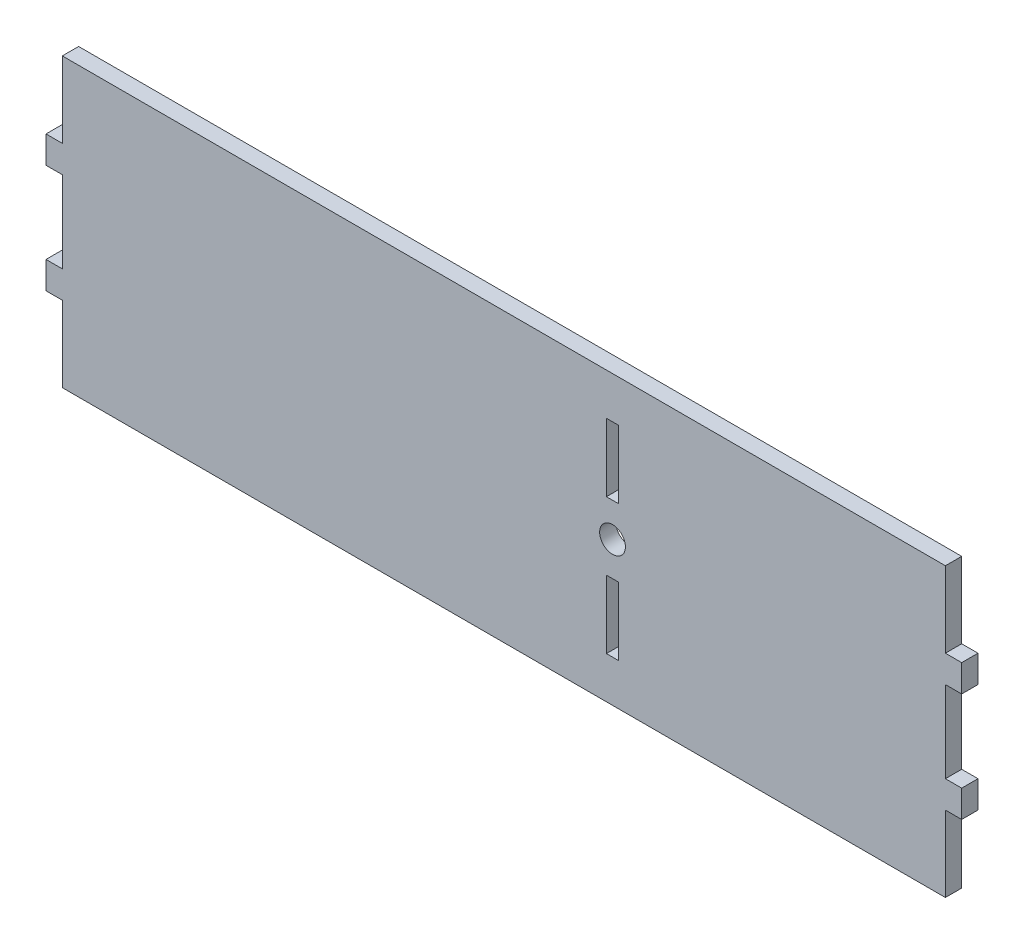
SolidWorks part; units mm, degrees
ref_plane "Front Plane" through (0, 0, 0) normal (0, 0, 1) x (1, 0, 0)
ref_plane "Top Plane" through (0, 0, 0) normal (0, 1, 0) x (1, 0, 0)
ref_plane "Right Plane" through (0, 0, 0) normal (1, 0, 0) x (0, 0, -1)
sketch "Sketch1" plane through (0, 0, 0) normal (0, 0, 1) x (1, 0, 0)
  line L0 (-65, 21.15) -> (-65, 10)
  line L1 (65, 21.15) -> (-65, 21.15)
  line L2 (65, 21.15) -> (65, -21.15)
  line L3 (65, -21.15) -> (-65, -21.15)
  line L4 (-65, 21.15) -> (-65, -21.15)
  line L5 (65, 21.15) -> (-65, -21.15) construction
  line L6 (65, -21.15) -> (-65, 21.15) construction
  line L7 (-65, 10) -> (-67.4, 10)
  line L8 (-67.4, 10) -> (-67.4, 6)
  line L9 (-67.4, 6) -> (-65, 6)
  line L10 (-65, 0) -> (65, 0)
  line L11 (-65, -10) -> (-67.4, -10)
  line L12 (-67.4, -10) -> (-67.4, -6)
  line L13 (-67.4, -6) -> (-65, -6)
  line L14 (0, 21.15) -> (0, -21.15)
  line L15 (65, -10) -> (67.4, -10)
  line L16 (67.4, -10) -> (67.4, -6)
  line L17 (67.4, -6) -> (65, -6)
  line L18 (67.4, 6) -> (65, 6)
  line L19 (67.4, 10) -> (67.4, 6)
  line L20 (65, 10) -> (67.4, 10)
  line L21 (0, 0) -> (16, 0)
  line L22 (16, 0) -> (16, 10)
  line L23 (16.9, -5) -> (15.1, -5)
  line L24 (16.9, 15) -> (15.1, 15)
  line L25 (16.9, 15) -> (16.9, 5)
  line L26 (16.9, 5) -> (15.1, 5)
  line L27 (15.1, 15) -> (15.1, 5)
  line L28 (16.9, 15) -> (15.1, 5) construction
  line L29 (16.9, 5) -> (15.1, 15) construction
  line L30 (16.9, -15) -> (15.1, -15)
  line L31 (16.9, -15) -> (16.9, -5)
  line L32 (15.1, -15) -> (15.1, -5)
  circle A0 centre (16, 0) radius 1.9
  point P0 (0, 0)
extrude "Boss-Extrude1" add sketch "Sketch1" along normal blind 2.4 contours L8 L9 L4 L7 | L14 L1 L0 L4 L10 | L14 L10 L4 L3 | L13 L12 L11 L4 | L10 L14 L3 L2 | L1 L14 L10 L2 | L20 L2 L18 L19 | L16 L17 L2 L15
